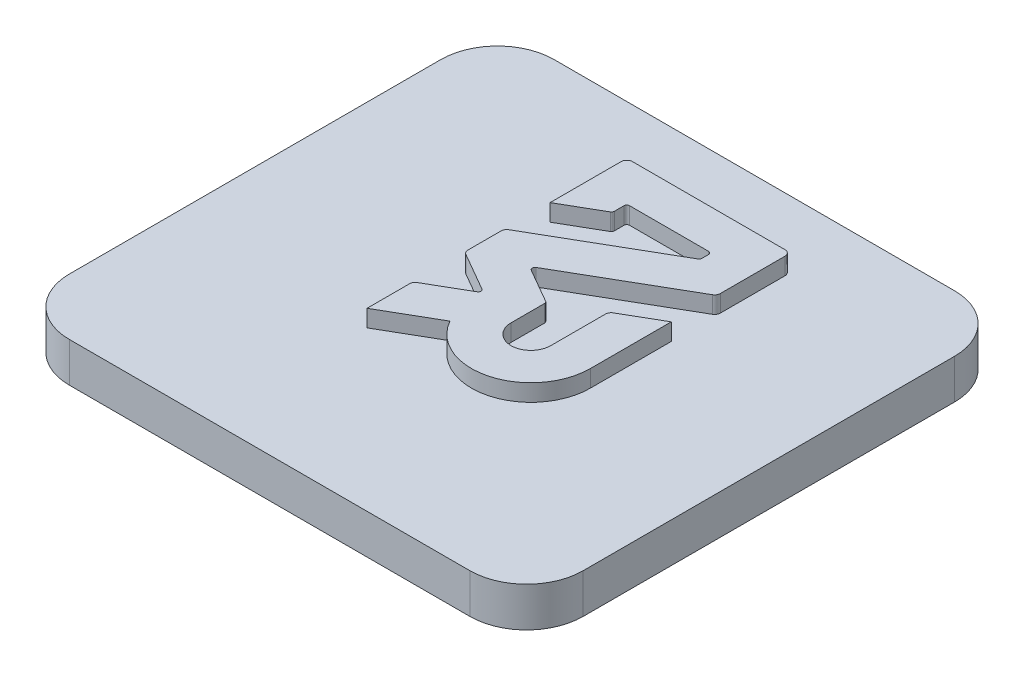
SolidWorks part; units mm, degrees
ref_plane "Front Plane" through (0, 0, 0) normal (0, 0, 1) x (1, 0, 0)
ref_plane "Top Plane" through (0, 0, 0) normal (0, 1, 0) x (1, 0, 0)
ref_plane "Right Plane" through (0, 0, 0) normal (1, 0, 0) x (0, 0, -1)
sketch "Sketch1" plane through (0, 0, 0) normal (0, 1, 0) x (1, 0, 0)
  line L0 (5.501, 17.7744) -> (96.2581, 17.7744)
  line L1 (5.501, 17.7744) -> (5.501, -67.8461)
  line L2 (96.2581, 17.7744) -> (96.2581, -67.8461)
  line L3 (5.501, -67.8461) -> (96.2581, -67.8461)
extrude "Boss-Extrude1" add sketch "Sketch1" along normal blind 10
sketch "Sketch2" plane through (0, 10, 0) normal (0, 1, 0) x (1, 0, 0)
  line L6 (68.9723, 6.0834) -> (40.0344, 6.0834) construction
  line L8 (68.9723, 6.0834) -> (68.9723, -39.7896) construction
  line L11 (40.0344, 6.0834) -> (40.0344, -39.7896) construction
  line L12 (68.9723, -39.7896) -> (40.0344, -39.7896) construction
  line L13 (68.9723, 5.0834) -> (68.9723, -6.3392)
  line L14 (67.9723, 6.0834) -> (41.0344, 6.0834)
  line L15 (68.9723, -6.9166) -> (40.0344, -6.9166) construction
  line L16 (40.0344, 5.0834) -> (40.0344, -6.9166)
  line L17 (68.9723, -14.9995) -> (62.4723, -18.7523)
  line L18 (54.9723, -23.0824) -> (40.5344, -31.4181)
  line L19 (68.9723, -14.9995) -> (68.9723, -29.2896)
  line L25 (40.0344, -32.2841) -> (40.0344, -39.7896)
  line L26 (40.0344, -39.7896) -> (47.9723, -35.2067)
  line L28 (47.9723, -35.2067) -> (47.9723, -29.2896) construction
  line L29 (61.9723, -19.6183) -> (61.9723, -29.2896)
  line L30 (68.9723, -29.2896) -> (47.9723, -29.2896) construction
  line L31 (54.9723, -23.0824) -> (54.9723, -29.2896)
  line L32 (61.9723, -29.2896) -> (54.9723, -29.2896) construction
  line L33 (40.5344, -15.2523) -> (61.7223, -3.0195)
  line L34 (40.0344, -6.9166) -> (40.0344, -15.5409) construction
  line L35 (68.9723, -39.7896) -> (40.0344, -39.7896) construction
  line L36 (40.0344, -16.1183) -> (40.0344, -21.9636)
  line L37 (47.9723, -35.2067) -> (49.3168, -34.4304)
  line L38 (5.501, 6.0834) -> (40.0344, 6.0834) construction
  line L39 (5.501, 17.7744) -> (5.501, -67.8461) construction
  line L40 (68.4723, -7.2052) -> (48.7223, -18.6079)
  line L41 (68.9723, 6.0834) -> (96.2581, 6.0834) construction
  line L42 (96.2581, -67.8461) -> (96.2581, 17.7744) construction
  line L43 (68.9723, 17.7744) -> (68.9723, 6.0834) construction
  line L44 (96.2581, 17.7744) -> (5.501, 17.7744) construction
  line L45 (47.0344, -1.4166) -> (47.0344, -3.1279)
  line L46 (68.9723, -39.7896) -> (68.9723, -67.8461) construction
  line L47 (5.501, -67.8461) -> (96.2581, -67.8461) construction
  line L48 (48.7223, -19.4739) -> (54.9723, -23.0824)
  line L49 (47.9723, -27.1238) -> (40.5344, -22.8296)
  line L50 (46.7844, -3.5609) -> (40.0344, -7.458)
  line L51 (40.0344, -7.458) -> (40.0344, -6.9166)
  line L52 (47.5344, -0.9166) -> (61.4723, -0.9166)
  line L53 (61.9723, -1.4166) -> (61.9723, -2.5864)
  line L54 (68.9723, -0.9166) -> (61.9723, -0.9166) construction
  line L55 (47.0344, -0.9166) -> (40.0344, -0.9166) construction
  line L56 (40.0344, 6.0834) -> (68.9723, 6.0834) construction
  line L57 (68.9723, 6.0834) -> (68.9723, -39.7896) construction
  arc A0 (68.9723, -29.2896) -> (47.9723, -29.2896) centre (58.4723, -29.2896) cw
  arc A1 (61.9723, -29.2896) -> (54.9723, -29.2896) centre (58.4723, -29.2896) cw
  arc A2 (62.4723, -18.7523) -> (61.9723, -19.6183) centre (62.9723, -19.6183) ccw
  arc A5 (68.4723, -7.2052) -> (68.9723, -6.3392) centre (67.9723, -6.3392) ccw
  arc A6 (68.9723, 5.0834) -> (67.9723, 6.0834) centre (67.9723, 5.0834) ccw
  arc A7 (40.5344, -31.4181) -> (40.0344, -32.2841) centre (41.0344, -32.2841) ccw
  arc A8 (41.0344, 6.0834) -> (40.0344, 5.0834) centre (41.0344, 5.0834) ccw
  arc A9 (40.0344, -16.1183) -> (40.5344, -15.2523) centre (41.0344, -16.1183) cw
  arc A10 (40.5344, -22.8296) -> (40.0344, -21.9636) centre (41.0344, -21.9636) cw
  arc A11 (47.5344, -0.9166) -> (47.0344, -1.4166) centre (47.5344, -1.4166) ccw
  arc A12 (46.7844, -3.5609) -> (47.0344, -3.1279) centre (46.5344, -3.1279) ccw
  arc A13 (61.9723, -1.4166) -> (61.4723, -0.9166) centre (61.4723, -1.4166) ccw
  arc A14 (61.7223, -3.0195) -> (61.9723, -2.5864) centre (61.4723, -2.5864) ccw
  arc A15 (48.7223, -19.4739) -> (48.7223, -18.6079) centre (48.9723, -19.0409) cw
  dimension "D8" = 1
  dimension "D12" = 7
  dimension "D13" = 0.5
  dimension "D1" = 1
  dimension "D2" = 1
  dimension "D9" = 0.5
  dimension "D3" = 7
  dimension "D4" = 7
  dimension "D5" = 7
  dimension "D6" = 7
  dimension "D7" = 30
  dimension "D10" = 30
  dimension "D11" = 7
extrude "Cut-Extrude1" cut sketch "Sketch2" against normal blind 3
fillet "Fillet3" radius 10 4 edges at (96.2581, 3.5, -17.7744) (5.501, 3.5, -17.7744) (5.501, 3.5, 67.8461) (96.2581, 3.5, 67.8461)
fillet "Fillet4" radius 0.5 2 edges at (54.9723, 8.5, 23.0824) (47.9723, 8.5, 27.1238)
